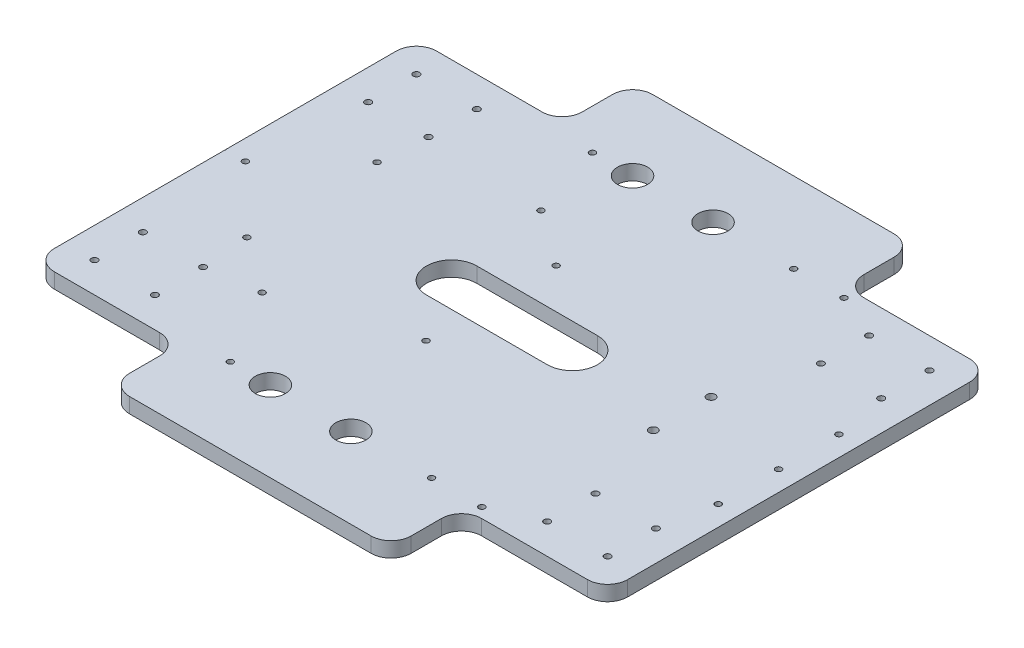
SolidWorks part; units mm, degrees
ref_plane "前视基准面" through (0, 0, 0) normal (0, 0, 1) x (1, 0, 0)
ref_plane "上视基准面" through (0, 0, 0) normal (0, 1, 0) x (1, 0, 0)
ref_plane "右视基准面" through (0, 0, 0) normal (1, 0, 0) x (0, 0, -1)
sketch "草图1" plane through (0, 0, 0) normal (0, 1, 0) x (1, 0, 0)
  line L1 (-150, 150) -> (150, 150)
  line L2 (-150, 150) -> (-150, -150)
  line L3 (-150, -150) -> (150, -150)
  line L4 (150, 150) -> (150, -150)
  line L5 (-150, 150) -> (150, -150) construction
  line L6 (-150, -150) -> (150, 150) construction
  point P0 (0, 0)
  dimension "D1" = 300
  dimension "D2" = 300
extrude "凸台-拉伸1" add sketch "草图1" along normal blind 7.5
sketch "草图2" plane through (0, 0, 0) normal (0, -1, 0) x (-1, 0, 0)
  line L0 (-207.2489, 0) -> (207.5166, 0) construction
  line L1 (0, -223.7694) -> (0, 371.3951) construction
  line L2 (-150, -100) -> (-70, -100)
  line L3 (-150, -150) -> (-150, 150) construction
  line L4 (150, -150) -> (-150, -150) construction
  line L5 (-150, 100) -> (-70, 100)
  line L6 (-150, 150) -> (150, 150) construction
  line L7 (150, -100) -> (70, -100)
  line L8 (150, 150) -> (150, -150) construction
  line L9 (150, 100) -> (70, 100)
  line L10 (-70, 100) -> (-70, 150)
  line L11 (-70, 150) -> (-150, 150)
  line L12 (70, 150) -> (70, 100)
  line L13 (-70, -100) -> (-70, -150)
  line L14 (-70, -150) -> (-150, -150)
  line L15 (-150, -150) -> (-150, -100)
  line L16 (-150, 150) -> (-150, 100)
  line L17 (70, 150) -> (150, 150)
  line L18 (150, 150) -> (150, 100)
  line L19 (70, -100) -> (70, -150)
  line L20 (70, -150) -> (150, -150)
  line L21 (150, -150) -> (150, -100)
  dimension "D1" = 50
  dimension "D2" = 50
  dimension "D3" = 80
  dimension "D4" = 80
  dimension "D5" = 80
  dimension "D6" = 80
extrude "切除-拉伸1" cut sketch "草图2" against normal blind 50
sketch "草图3" plane through (0, 0, 0) normal (0, -1, 0) x (1, 0, 0)
  circle A0 centre (132.5, 81.5057) radius 1.6
  circle A1 centre (132.5, 57.5057) radius 1.6
  circle A2 centre (102.5, 81.5057) radius 1.6
  circle A3 centre (102.5, 57.5057) radius 1.6
  circle A4 centre (-102.5, 81.5057) radius 1.6
  circle A5 centre (-102.5, 57.5057) radius 1.6
  circle A6 centre (-132.5, 81.5057) radius 1.6
  circle A7 centre (-132.5, 57.5057) radius 1.6
  circle A8 centre (-132.5, -57.5057) radius 1.6
  circle A9 centre (-132.5, -81.5057) radius 1.6
  circle A10 centre (-102.5, -57.5057) radius 1.6
  circle A11 centre (-102.5, -81.5057) radius 1.6
  circle A12 centre (132.5, -81.5057) radius 1.6
  circle A13 centre (132.5, -57.5057) radius 1.6
  circle A14 centre (102.5, -57.5057) radius 1.6
  circle A15 centre (102.5, -81.5057) radius 1.6
extrude "切除-拉伸2" cut sketch "草图3" against normal blind 500
sketch "草图5" plane through (0, 0, 0) normal (0, -1, 0) x (1, 0, 0)
  line L0 (145.7796, 0) -> (141.6899, 4.0897)
  line L1 (141.6899, 4.0897) -> (141.6899, -4.0897)
  line L2 (141.6899, -4.0897) -> (145.7796, 0)
extrude "切除-拉伸4" cut sketch "草图5" against normal blind 0.01
sketch "草图6" plane through (0, 7.5, 0) normal (0, 1, 0) x (1, 0, 0)
  line L0 (-70, 150) -> (70, 150)
  line L1 (70, 150) -> (70, 145)
  line L2 (70, 150) -> (70, 100) construction
  line L3 (70, 145) -> (-70, 145)
  line L4 (-70, 100) -> (-70, 150) construction
  line L5 (-70, 145) -> (-70, 150)
  dimension "D1" = 5
extrude "切除-拉伸5" cut sketch "草图6" against normal blind 400
sketch "草图7" plane through (0, 7.5, 0) normal (0, 1, 0) x (1, 0, 0)
  line L0 (-70, -150) -> (70, -150)
  line L1 (70, -150) -> (70, -145)
  line L2 (70, -100) -> (70, -150) construction
  line L3 (70, -145) -> (-70, -145)
  line L4 (-70, -150) -> (-70, -100) construction
  line L5 (-70, -145) -> (-70, -150)
  dimension "D1" = 5
extrude "切除-拉伸6" cut sketch "草图7" against normal blind 500
sketch "草图8" plane through (0, 7.5, 0) normal (0, 1, 0) x (1, 0, 0)
  line L0 (-150, 100) -> (-150, -100)
  line L1 (-150, -100) -> (-147.5, -100)
  line L2 (-70, -100) -> (-150, -100) construction
  line L3 (-147.5, -100) -> (-147.5, 100)
  line L4 (-150, 100) -> (-70, 100) construction
  line L5 (-147.5, 100) -> (-150, 100)
  dimension "D1" = 2.5
extrude "切除-拉伸7" cut sketch "草图8" against normal blind 500
sketch "草图9" plane through (0, 7.5, 0) normal (0, 1, 0) x (1, 0, 0)
  line L0 (150, -100) -> (70, -100) construction
  line L1 (150, 100) -> (147.5, 100)
  line L2 (150, 100) -> (150, -100)
  line L3 (150, -100) -> (147.5, -100)
  line L4 (147.5, 100) -> (147.5, -100)
  dimension "D1" = 2.5
extrude "切除-拉伸8" cut sketch "草图9" against normal blind 500
fillet "圆角1" radius 10 2 edges at (70, 3.75, 145) (-70, 3.75, 145)
fillet "圆角2" radius 10 2 edges at (-70, 3.75, 100) (70, 3.75, 100)
fillet "圆角3" radius 10 2 edges at (147.5, 3.75, 100) (-147.5, 3.75, 100)
fillet "圆角4" radius 10 2 edges at (147.5, 3.75, -100) (-147.5, 3.75, -100)
fillet "圆角5" radius 10 2 edges at (-70, 3.75, -100) (70, 3.75, -100)
fillet "圆角6" radius 10 2 edges at (70, 3.75, -145) (-70, 3.75, -145)
sketch "草图11" plane through (0, 0, 0) normal (0, -1, 0) x (1, 0, 0)
  circle A0 centre (-50, 125) radius 1.5
extrude "切除-拉伸9" cut sketch "草图11" against normal blind 500
sketch "草图12" plane through (0, 0, 0) normal (0, -1, 0) x (1, 0, 0)
  circle A0 centre (50, 125) radius 1.5
  circle A1 centre (70, 80) radius 1.5
  circle A2 centre (70, 0) radius 1.5
  circle A3 centre (70, -80) radius 1.5
  circle A4 centre (50, -125) radius 1.5
  circle A5 centre (-50, -125) radius 1.5
  circle A6 centre (-82.5, -85) radius 1.5
  circle A7 centre (-132.5, 0) radius 1.5
  circle A8 centre (-50, 125) radius 1.5
  circle A9 centre (-82.5, 85) radius 1.5
extrude "切除-拉伸10" cut sketch "草图12" against normal blind 500
sketch "草图13" plane through (0, 7.5, 0) normal (0, 1, 0) x (1, 0, 0)
  line L0 (0, 223.8035) -> (0, -237.5015) construction
  line L1 (0, -20) -> (0, 20) construction
  line L4 (-10, -20) -> (-10, 20)
  line L5 (10, -20) -> (10, 20)
  arc A2 (-10, -20) -> (10, -20) centre (0, -20) ccw
  arc A3 (10, 20) -> (-10, 20) centre (0, 20) ccw
  point P5 (0, 0)
  dimension "D1" = 40
  dimension "D2" = 20
extrude "切除-拉伸11" cut sketch "草图13" against normal blind 50
sketch "草图14" plane through (0, 7.5, 0) normal (0, 1, 0) x (1, 0, 0)
  circle A0 centre (-82.5, 85) radius 5.7823
  circle A1 centre (-50, 125) radius 5.2485
  circle A2 centre (50, 125) radius 6.2753
  circle A3 centre (69.6105, 80.2788) radius 6.5098
  circle A4 centre (70, 0) radius 6.5732
  circle A5 centre (70, -80) radius 7.1651
  circle A6 centre (-50, -125) radius 4.8884
  circle A7 centre (49.5183, -125) radius 5.8066
  circle A8 centre (-82.5, -85) radius 4.2392
extrude "凸台-拉伸2" add sketch "草图14" against normal up to surface (7.5 mm away) up to face at (0, 0, 0)
sketch "草图15" plane through (0, 7.5, 0) normal (0, 1, 0) x (1, 0, 0)
  circle A0 centre (-132.5, 0) radius 3.4468
extrude "凸台-拉伸3" add sketch "草图15" against normal up to surface (7.5 mm away) up to face at (0, 0, 0)
sketch "草图16" plane through (0, 0, 0) normal (0, -1, 0) x (1, 0, 0)
  line L1 (-28.5147, 54.5247) -> (28.5147, 54.5247)
  line L2 (-28.5147, 54.5247) -> (-28.5147, -54.5247)
  line L3 (-28.5147, -54.5247) -> (28.5147, -54.5247)
  line L4 (28.5147, 54.5247) -> (28.5147, -54.5247)
  line L5 (-28.5147, 54.5247) -> (28.5147, -54.5247) construction
  line L6 (-28.5147, -54.5247) -> (28.5147, 54.5247) construction
  point P0 (0, 0)
extrude "凸台-拉伸4" add sketch "草图16" against normal up to surface (7.5 mm away) up to face at (0, 7.5, 0)
sketch "草图17" plane through (0, 0, 0) normal (0, -1, 0) x (1, 0, 0)
  line L0 (-30, 0) -> (30, 0) construction
  line L1 (-30, 12.5) -> (30, 12.5)
  line L2 (-30, -12.5) -> (30, -12.5)
  arc A0 (-30, 12.5) -> (-30, -12.5) centre (-30, 0) ccw
  arc A1 (30, -12.5) -> (30, 12.5) centre (30, 0) ccw
  point P2 (0, 0)
  dimension "D1" = 25
  dimension "D2" = 60
extrude "切除-拉伸12" cut sketch "草图17" against normal blind 30
sketch "草图18" plane through (0, 0, 0) normal (0, -1, 0) x (1, 0, 0)
  line L0 (-185.4456, 0) -> (208.4346, 0) construction
  line L1 (0, 244.2865) -> (0, -260.0726) construction
  line L2 (147.5, -90) -> (147.5, 90) construction
  line L3 (-147.5, 90) -> (-147.5, -90) construction
  line L4 (-60, -145) -> (60, -145) construction
  line L5 (60, 145) -> (-60, 145) construction
  circle A2 centre (-55, 137) radius 1.5
  circle A3 centre (55, 137) radius 1.5
  circle A4 centre (-137.5, 0) radius 1.5
  circle A5 centre (137.5, 0) radius 1.5
  circle A6 centre (-55, -137) radius 1.5
  circle A7 centre (55, -137) radius 1.5
  dimension "D1" = 3
  dimension "D3" = 10
  dimension "D4" = 55
  dimension "D5" = 8
  dimension "D6" = 8
  dimension "D7" = 55
  dimension "D11" = 8
  dimension "D12" = 8
  dimension "D2" = 10
  dimension "D8" = 393.8802
  dimension "D9" = 55
  dimension "D10" = 55
extrude "切除-拉伸13" cut sketch "草图18" against normal blind 10
sketch "草图19" plane through (0, 0, 0) normal (0, -1, 0) x (1, 0, 0)
  line L0 (140.38, 6.1809) -> (140.6108, -5.888)
  line L1 (140.6108, -5.888) -> (146.9421, -3.8436)
  line L2 (146.9421, -3.8436) -> (146.5793, 2.3557)
  line L3 (146.5793, 2.3557) -> (140.38, 6.1809)
extrude "凸台-拉伸5" add sketch "草图19" against normal up to surface (7.5 mm away) up to face at (-55, 7.5, -135.5)
sketch "草图20" plane through (0, 0, 0) normal (0, -1, 0) x (1, 0, 0)
  line L0 (147.5, -90) -> (147.5, 90) construction
  circle A0 centre (147.5, 0) radius 0.5
  dimension "D1" = 1
extrude "切除-拉伸14" cut sketch "草图20" against normal blind 1000
sketch "草图21" plane through (0, 0, 0) normal (0, -1, 0) x (1, 0, 0)
  line L0 (-193.9892, 0) -> (198.8819, 0) construction
  line L1 (0, 235.1962) -> (0, -194.108) construction
  line L2 (60, 145) -> (-60, 145) construction
  line L4 (-65, 140) -> (65, 140)
  line L5 (-142.5, 95) -> (-142.5, -95)
  line L6 (-65, -140) -> (65, -140)
  line L7 (142.5, 95) -> (142.5, -95)
  line L8 (147.5, 0.5) -> (147.5, 90) construction
  line L9 (-147.5, 90) -> (-147.5, -90) construction
  line L10 (-60, -145) -> (60, -145) construction
  line L11 (-80, -100) -> (-137.5, -100) construction
  line L14 (-142.5, -95) -> (-65, -95)
  line L15 (-65, -140) -> (-65, -95)
  line L16 (-70, -135) -> (-70, -110) construction
  line L17 (-137.5, 100) -> (-80, 100) construction
  line L20 (142.5, -95) -> (65, -95)
  line L21 (65, -140) -> (65, -95)
  line L24 (142.5, 95) -> (65, 95)
  line L25 (65, 140) -> (65, 95)
  line L28 (-142.5, 95) -> (-65, 95)
  line L29 (-65, 140) -> (-65, 95)
  line L30 (-70, 110) -> (-70, 135) construction
  line L31 (70, 135) -> (70, 110) construction
  line L32 (80, 100) -> (137.5, 100) construction
  line L33 (137.5, -100) -> (80, -100) construction
  line L34 (70, -110) -> (70, -135) construction
  dimension "D1" = 5
  dimension "D2" = 5
  dimension "D3" = 5
  dimension "D4" = 5
  dimension "D5" = 5
  dimension "D6" = 5
  dimension "D7" = 5
  dimension "D8" = 5
  dimension "D9" = 5
  dimension "D10" = 5
  dimension "D11" = 5
  dimension "D12" = 5
extrude "切除-拉伸15" cut sketch "草图21" against normal through all both and the other way through all flip side to cut
sketch "草图23" plane through (0, 0, 0) normal (0, -1, 0) x (1, 0, 0)
  line L1 (81.885, -46.0618) -> (138.1127, -46.0618)
  line L2 (81.885, -46.0618) -> (81.885, -87.4844)
  line L3 (81.885, -87.4844) -> (138.1127, -87.4844)
  line L4 (138.1127, -46.0618) -> (138.1127, -87.4844)
  line L5 (86.5288, 88.9059) -> (138.1127, 88.9059)
  line L6 (86.5288, 88.9059) -> (86.5288, 49.187)
  line L7 (86.5288, 49.187) -> (138.1127, 49.187)
  line L8 (138.1127, 88.9059) -> (138.1127, 49.187)
  line L9 (-137.805, 88.9059) -> (-85.2394, 88.9059)
  line L10 (-137.805, 88.9059) -> (-137.805, 44.7917)
  line L11 (-137.805, 44.7917) -> (-85.2394, 44.7917)
  line L12 (-85.2394, 88.9059) -> (-85.2394, 44.7917)
  circle A0 centre (-132.5, -57.5057) radius 4.616
  circle A1 centre (-102.5, -57.5057) radius 4.0867
  circle A2 centre (-132.5, -81.5057) radius 3.6245
  circle A3 centre (-102.5, -81.5057) radius 3.9781
extrude "凸台-拉伸6" add sketch "草图23" against normal up to surface (7.5 mm away) up to face at (132.5, 7.5, 83.1057)
sketch "草图22" plane through (0, 0, 0) normal (0, -1, 0) x (1, 0, 0)
  line L0 (-142.5, -95) -> (-142.5, 95) construction
  line L1 (-142.5, 95) -> (-65, 95) construction
  line L2 (-127.5, 80) -> (-97.5, 80) construction
  line L3 (-127.5, 80) -> (-127.5, 56) construction
  line L4 (-127.5, 56) -> (-97.5, 56) construction
  line L5 (-97.5, 80) -> (-97.5, 56) construction
  line L6 (0, 211.7342) -> (0, -195.4074) construction
  line L7 (97.5, 80) -> (97.5, 56) construction
  line L8 (127.5, 56) -> (97.5, 56) construction
  line L9 (127.5, 80) -> (127.5, 56) construction
  line L10 (127.5, 80) -> (97.5, 80) construction
  line L11 (-237.0155, 0) -> (200.2362, 0) construction
  line L12 (-97.5, -80) -> (-97.5, -56) construction
  line L13 (-127.5, -56) -> (-97.5, -56) construction
  line L14 (-127.5, -80) -> (-127.5, -56) construction
  line L15 (-127.5, -80) -> (-97.5, -80) construction
  line L16 (127.5, -80) -> (97.5, -80) construction
  line L17 (127.5, -80) -> (127.5, -56) construction
  line L18 (127.5, -56) -> (97.5, -56) construction
  line L19 (97.5, -80) -> (97.5, -56) construction
  line L20 (127.5, -80) -> (97.5, -80) construction
  line L21 (127.5, -80) -> (127.5, -56) construction
  line L22 (127.5, -56) -> (97.5, -56) construction
  line L23 (97.5, -80) -> (97.5, -56) construction
  line L24 (-97.5, -80) -> (-97.5, -56) construction
  line L25 (-127.5, -56) -> (-97.5, -56) construction
  line L26 (-127.5, -80) -> (-127.5, -56) construction
  line L27 (-127.5, -80) -> (-97.5, -80) construction
  circle A0 centre (-127.5, 80) radius 1.6
  circle A1 centre (-97.5, 80) radius 1.6
  circle A2 centre (-127.5, 56) radius 1.6
  circle A3 centre (-97.5, 56) radius 1.6
  circle A4 centre (97.5, 56) radius 1.6
  circle A5 centre (127.5, 56) radius 1.6
  circle A6 centre (127.5, 80) radius 1.6
  circle A7 centre (97.5, 80) radius 1.6
  circle A8 centre (97.5, -80) radius 1.6
  circle A9 centre (127.5, -80) radius 1.6
  circle A10 centre (127.5, -56) radius 1.6
  circle A11 centre (97.5, -56) radius 1.6
  circle A12 centre (-97.5, -56) radius 1.6
  circle A13 centre (-127.5, -56) radius 1.6
  circle A14 centre (-97.5, -80) radius 1.6
  circle A15 centre (-127.5, -80) radius 1.6
  dimension "D1" = 30
  dimension "D2" = 24
  dimension "D5" = 3.2
  dimension "D3" = 15
  dimension "D4" = 15
extrude "切除-拉伸16" cut sketch "草图22" against normal blind 1000
sketch "草图24" plane through (0, 0, 0) normal (0, -1, 0) x (1, 0, 0)
  line L1 (-140.6231, 4.4758) -> (-112.0676, 4.4758)
  line L2 (-140.6231, 4.4758) -> (-140.6231, -10.2346)
  line L3 (-140.6231, -10.2346) -> (-112.0676, -10.2346)
  line L4 (-112.0676, 4.4758) -> (-112.0676, -10.2346)
  line L5 (119.4378, 13.1302) -> (140.0386, 13.1302)
  line L6 (119.4378, 13.1302) -> (119.4378, -10.2346)
  line L7 (119.4378, -10.2346) -> (140.0386, -10.2346)
  line L8 (140.0386, 13.1302) -> (140.0386, -10.2346)
  line L9 (39.9786, -123.148) -> (61.4979, -123.148)
  line L10 (39.9786, -123.148) -> (39.9786, -139.2714)
  line L11 (39.9786, -139.2714) -> (61.4979, -139.2714)
  line L12 (61.4979, -123.148) -> (61.4979, -139.2714)
  line L13 (-58.2702, -131.6904) -> (-51.4144, -131.6904)
  line L14 (-58.2702, -131.6904) -> (-58.2702, -139.2714)
  line L15 (-58.2702, -139.2714) -> (-51.4144, -139.2714)
  line L16 (-51.4144, -131.6904) -> (-51.4144, -139.2714)
  line L17 (-41.3322, 128.4597) -> (-59.9751, 128.4597)
  line L18 (-41.3322, 128.4597) -> (-41.3322, 138.7926)
  line L19 (-41.3322, 138.7926) -> (-59.9751, 138.7926)
  line L20 (-59.9751, 128.4597) -> (-59.9751, 138.7926)
  line L21 (48.6028, 132.9442) -> (61.4979, 132.9442)
  line L22 (48.6028, 132.9442) -> (48.6028, 138.7926)
  line L23 (48.6028, 138.7926) -> (61.4979, 138.7926)
  line L24 (61.4979, 132.9442) -> (61.4979, 138.7926)
extrude "凸台-拉伸7" add sketch "草图24" against normal up to surface (7.5 mm away) up to face at (97.5, 7.5, -78.4)
sketch "草图25" plane through (0, 0, 0) normal (0, -1, 0) x (1, 0, 0)
  line L0 (0, 217.3609) -> (0, -227.0091) construction
  line L1 (-251.8118, 0) -> (274.3346, 0) construction
  line L3 (-65, 140) -> (65, 140) construction
  line L4 (-142.5, -95) -> (-142.5, 95) construction
  line L5 (142.5, 95) -> (142.5, -95) construction
  circle A0 centre (-50, 132) radius 1.5
  circle A1 centre (50, 132) radius 1.5
  circle A2 centre (-132.5, 0) radius 1.5
  circle A3 centre (132.5, 0) radius 1.5
  circle A6 centre (50, -132) radius 1.5
  circle A7 centre (-50, -132) radius 1.5
  dimension "D1" = 3
  dimension "D3" = 8
  dimension "D5" = 8
  dimension "D6" = 10
  dimension "D7" = 10
  dimension "D2" = 50
  dimension "D4" = 50
extrude "切除-拉伸17" cut sketch "草图25" against normal blind 100
fillet "圆角7" radius 10 6 edges at (142.5, 3.75, 95) (65, 3.75, 95) (65, 3.75, 140) (-65, 3.75, 140) (-142.5, 3.75, 95) (-65, 3.75, 95)
fillet "圆角8" radius 10 6 edges at (142.5, 3.75, -95) (65, 3.75, -95) (65, 3.75, -140) (-65, 3.75, -140) (-65, 3.75, -95) (-142.5, 3.75, -95)
sketch "草图26" plane through (0, 7.5, 0) normal (0, 1, 0) x (1, 0, 0)
  line L0 (-142.5, -85) -> (-142.5, 85) construction
  circle A0 centre (-142.5, 0) radius 0.25
  dimension "D1" = 0.5
extrude "切除-拉伸18" cut sketch "草图26" against normal blind 10
sketch "草图28" plane through (0, 7.5, 0) normal (0, 1, 0) x (1, 0, 0)
  line L0 (-132.5, 95) -> (132.5, 95)
  line L1 (132.5, 95) -> (99.5771, 183.3236)
  line L2 (99.5771, 183.3236) -> (-104.8704, 176.9346)
  line L3 (-104.8704, 176.9346) -> (-132.5, 95)
  line L4 (-86.6386, -95) -> (91.6448, -95)
  line L5 (-75, -95) -> (-132.5, -95) construction
  line L6 (132.5, -95) -> (75, -95) construction
  line L7 (91.6448, -95) -> (76.3222, -162.5082)
  line L8 (76.3222, -162.5082) -> (-68.2265, -151.8445)
  line L9 (-68.2265, -151.8445) -> (-86.6386, -95)
extrude "切除-拉伸19" cut sketch "草图28" against normal blind 10
sketch "草图29" plane through (0, 0, 0) normal (0, -1, 0) x (1, 0, 0)
  circle A0 centre (-50, -90) radius 1.5
  circle A1 centre (50, -90) radius 1.5
extrude "切除-拉伸20" cut sketch "草图29" against normal blind 200
mirror "镜向1" about plane through (0, 0, 0) normal (0, 0, 1) of "切除-拉伸20"
sketch "草图30" plane through (0, 7.5, 0) normal (0, 1, 0) x (1, 0, 0)
  line L0 (132.5, 0) -> (132.5, 280.8029) construction
  line L1 (132.5, 0) -> (132.5, -238.1885) construction
  line L2 (132.5, -95) -> (-132.5, -95) construction
  line L3 (-132.5, 95) -> (132.5, 95) construction
  circle A0 centre (132.5, 30) radius 1.5
  circle A1 centre (132.5, -30) radius 1.5
  dimension "D1" = 3
  dimension "D2" = 3
  dimension "D3" = 65
  dimension "D4" = 65
extrude "切除-拉伸21" cut sketch "草图30" against normal blind 200
sketch "草图31" plane through (0, 7.5, 0) normal (0, 1, 0) x (1, 0, 0)
  line L0 (50, 90) -> (75, 90) construction
  line L1 (50, -90) -> (75, -90) construction
  circle A0 centre (75, 90) radius 1.5
  circle A1 centre (75, -90) radius 1.5
  dimension "D2" = 3
  dimension "D4" = 3
  dimension "D1" = 25
  dimension "D3" = 25
extrude "切除-拉伸22" cut sketch "草图31" against normal blind 15
sketch "草图32" plane through (0, 7.5, 0) normal (0, 1, 0) x (1, 0, 0)
  line L0 (75, 90) -> (75, -90) construction
  circle A0 centre (75, 0) radius 2
  dimension "D1" = 4
extrude "切除-拉伸23" cut sketch "草图32" against normal blind 15
sketch "草图33" plane through (0, 7.5, 0) normal (0, 1, 0) x (1, 0, 0)
  circle A0 centre (-99.4134, 32.3282) radius 1.5
  circle A1 centre (-37.9215, 52.3081) radius 1.5
  circle A2 centre (-10.4215, 32.3282) radius 1.5
  circle A3 centre (-10.4215, -32.3282) radius 1.5
  circle A4 centre (-71.9134, -52.3081) radius 1.5
  circle A5 centre (-99.4134, -32.3282) radius 1.5
extrude "切除-拉伸24" cut sketch "草图33" against normal blind 10
sketch "草图34" plane through (0, 7.5, 0) normal (0, 1, 0) x (1, 0, 0)
  line L0 (132.5, -95) -> (-132.5, -95) construction
  line L1 (-70.0816, -95) -> (69.9184, -95)
  line L2 (-70.0816, -95) -> (-70.0816, -130)
  line L3 (-70.0816, -130) -> (69.9184, -130)
  line L4 (69.9184, -95) -> (69.9184, -130)
  line L5 (-215.0764, 0) -> (262.414, 0) construction
  line L6 (69.9184, 95) -> (69.9184, 130)
  line L7 (-70.0816, 130) -> (69.9184, 130)
  line L8 (-70.0816, 95) -> (-70.0816, 130)
  line L9 (-70.0816, 95) -> (69.9184, 95)
  dimension "D1" = 140
  dimension "D2" = 35
extrude "凸台-拉伸8" add sketch "草图34" against normal blind 8
fillet "圆角9" radius 10 8 edges at (69.9184, 3.75, 95) (-70.0816, 3.75, 95) (-70.0816, 3.5, 130) (69.9184, 3.5, 130) (69.9184, 3.75, -95) (-70.0816, 3.75, -95) (-70.0816, 3.5, -130) (69.9184, 3.5, -130)
sketch "草图36" plane through (0, 7.5, 0) normal (0, 1, 0) x (1, 0, 0)
  circle A0 centre (9.9184, 90) radius 7.4839
extrude "切除-拉伸25" cut sketch "草图36" against normal blind 10
sketch "草图37" plane through (0, 7.5, 0) normal (0, 1, 0) x (1, 0, 0)
  circle A0 centre (9.9184, 90) radius 7.4839
  circle A1 centre (-30.0816, 90) radius 7.4839
  circle A2 centre (9.9184, -90) radius 7.4839
  circle A3 centre (-30.0816, -90) radius 7.4839
extrude "切除-拉伸26" cut sketch "草图37" against normal blind 10
sketch "草图38" plane through (0, 7.5, 0) normal (0, 1, 0) x (1, 0, 0)
  circle A0 centre (75, 0) radius 2
  circle A1 centre (84.6, -14.35) radius 2.1
extrude "切除-拉伸27" cut sketch "草图38" against normal blind 8
sketch "草图39" plane through (0, 7.5, 0) normal (0, 1, 0) x (1, 0, 0)
  circle A0 centre (84.6, 14.35) radius 2.1
extrude "切除-拉伸28" cut sketch "草图39" against normal blind 8
sketch "草图41" plane through (0, 7.5, 0) normal (0, 1, 0) x (1, 0, 0)
  circle A0 centre (75, 0) radius 2
extrude "凸台-拉伸9" add sketch "草图41" against normal blind 8
sketch "草图42" plane through (0, 0, 0) normal (0, -1, 0) x (1, 0, 0)
  line L1 (-198.5772, 150.6948) -> (198.5772, 150.6948)
  line L2 (-198.5772, 150.6948) -> (-198.5772, -150.6948)
  line L3 (-198.5772, -150.6948) -> (198.5772, -150.6948)
  line L4 (198.5772, 150.6948) -> (198.5772, -150.6948)
  line L5 (-198.5772, 150.6948) -> (198.5772, -150.6948) construction
  line L6 (-198.5772, -150.6948) -> (198.5772, 150.6948) construction
  point P0 (0, 0)
extrude "切除-拉伸29" cut sketch "草图42" along normal blind 10
